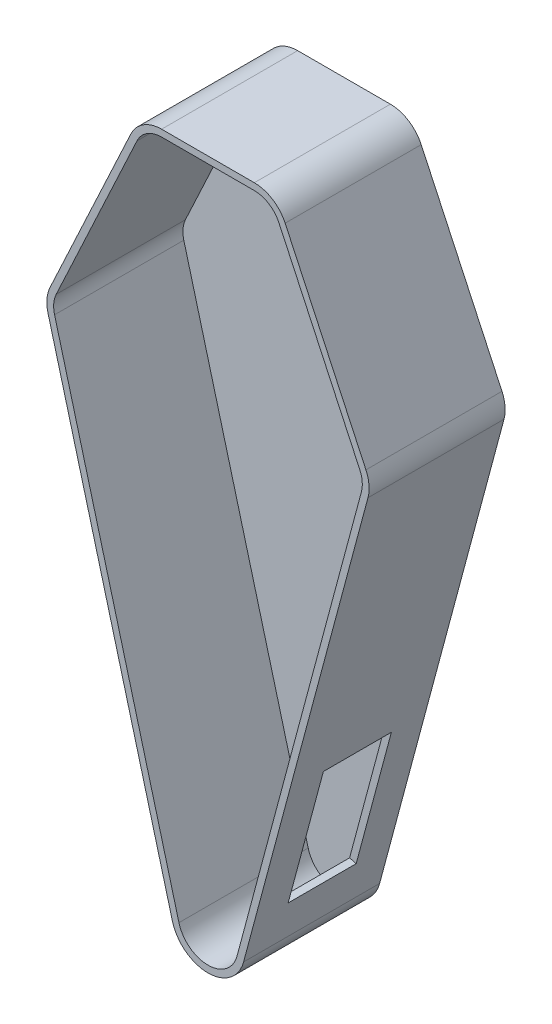
SolidWorks part; units mm, degrees
ref_plane "前视基准面" through (0, 0, 0) normal (0, 0, 1) x (1, 0, 0)
ref_plane "上视基准面" through (0, 0, 0) normal (0, 1, 0) x (1, 0, 0)
ref_plane "右视基准面" through (0, 0, 0) normal (1, 0, 0) x (0, 0, -1)
sketch "草图1" plane through (0, 0, 0) normal (0, 0, 1) x (1, 0, 0)
  line L0 (0, 0) -> (-20, 0)
  line L1 (-20, 0) -> (-33.9892, -30)
  line L2 (0, 0) -> (13.9892, -30)
  line L3 (-33.9892, -30) -> (-15.2328, -100)
  line L4 (13.9892, -30) -> (-4.7672, -100)
  line L5 (-33.9892, -30) -> (13.9892, -30) construction
  line L6 (-15.2328, -100) -> (-4.7672, -100) construction
  arc A0 (-15.2328, -100) -> (-4.7672, -100) centre (-10, -98.5979) ccw
  point P8 (-10, -30)
  dimension "D7" = 70
  dimension "D1" = 20
  dimension "D2" = 115
  dimension "D3" = 115
  dimension "D4" = 75
  dimension "D5" = 75
  dimension "D6" = 30
extrude "凸台-拉伸1" add sketch "草图1" along normal blind 20
fillet "圆角1" radius 5 4 edges at (-33.9892, -30, 10) (13.9892, -30, 10) (0, 0, 10) (-20, 0, 10)
shell "抽壳1" thickness 1
sketch "草图2" plane through (0, 0, 0) normal (0, 0, -1) x (-1, 0, 0)
  line L0 (3.1854, 0) -> (16.8146, 0) construction
  circle A0 centre (10, -12) radius 5
  point P5 (10, 0)
  dimension "D1" = 10
  dimension "D2" = 12
extrude "切除-拉伸1" cut sketch "草图2" against normal blind 20
sketch "草图3" plane through (20.5521, -5.5069, 0) normal (0.9659, -0.2588, 0) x (0, 0, -1)
  line L0 (-20, -97.8264) -> (0, -97.8264) construction
  line L1 (-15, -71.8264) -> (-5, -71.8264)
  line L2 (-15, -71.8264) -> (-15, -91.8264)
  line L3 (-15, -91.8264) -> (-5, -91.8264)
  line L4 (-5, -71.8264) -> (-5, -91.8264)
  line L5 (-15, -71.8264) -> (-5, -91.8264) construction
  line L6 (-15, -91.8264) -> (-5, -71.8264) construction
  line L7 (0, -97.8264) -> (0, -27.1769) construction
  point P4 (-10, -81.8264)
  dimension "D1" = 20
  dimension "D2" = 10
  dimension "D3" = 6
  dimension "D4" = 5
extrude "切除-拉伸2" cut sketch "草图3" against normal up to next
sketch "草图4" plane through (0, 0, 20) normal (0, 0, 1) x (1, 0, 0)
  line L33 (-33.5182, -31.7578) -> (-15.2328, -100)
  line L34 (-4.7672, -100) -> (13.5182, -31.7578)
  line L35 (-21.3462, -2.8869) -> (-33.2201, -28.3507)
  line L36 (13.2201, -28.3507) -> (1.3462, -2.8869)
  line L37 (-3.1854, 0) -> (-16.8146, 0)
  line L38 (-33.5182, -31.7578) -> (-15.2328, -100)
  line L39 (-4.7672, -100) -> (13.5182, -31.7578)
  line L40 (-21.3462, -2.8869) -> (-33.2201, -28.3507)
  line L41 (13.2201, -28.3507) -> (1.3462, -2.8869)
  line L42 (-3.1854, 0) -> (-16.8146, 0)
  arc A32 (-15.2328, -100) -> (-4.7672, -100) centre (-10, -98.5979) ccw
  arc A33 (13.5182, -31.7578) -> (13.2201, -28.3507) centre (8.6886, -30.4637) ccw
  arc A34 (-33.2201, -28.3507) -> (-33.5182, -31.7578) centre (-28.6886, -30.4637) ccw
  arc A35 (1.3462, -2.8869) -> (-3.1854, 0) centre (-3.1854, -5) ccw
  arc A36 (-16.8146, 0) -> (-21.3462, -2.8869) centre (-16.8146, -5) ccw
  arc A37 (-15.2328, -100) -> (-4.7672, -100) centre (-10, -98.5979) ccw
  arc A38 (13.5182, -31.7578) -> (13.2201, -28.3507) centre (8.6886, -30.4637) ccw
  arc A39 (-33.2201, -28.3507) -> (-33.5182, -31.7578) centre (-28.6886, -30.4637) ccw
  arc A40 (1.3462, -2.8869) -> (-3.1854, 0) centre (-3.1854, -5) ccw
  arc A41 (-16.8146, 0) -> (-21.3462, -2.8869) centre (-16.8146, -5) ccw
  dimension "D1" = 0
